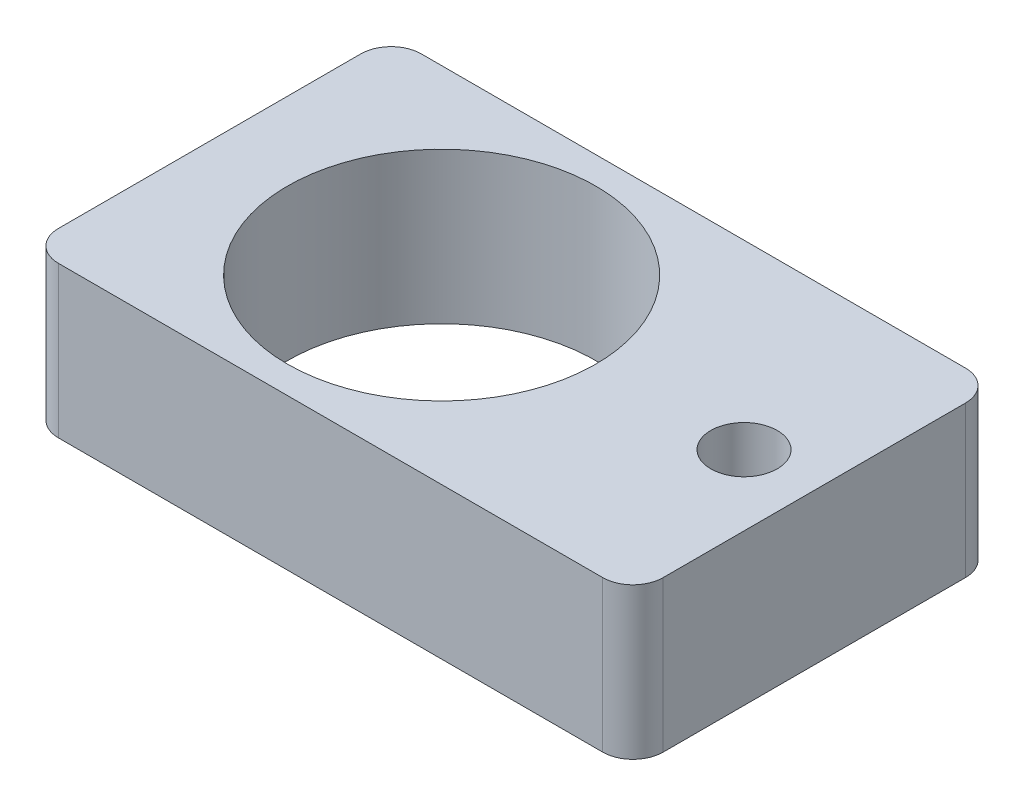
SolidWorks part; units mm, degrees
ref_plane "Front Plane" through (0, 0, 0) normal (0, 0, 1) x (1, 0, 0)
ref_plane "Top Plane" through (0, 0, 0) normal (0, 1, 0) x (1, 0, 0)
ref_plane "Right Plane" through (0, 0, 0) normal (1, 0, 0) x (0, 0, -1)
sketch "Sketch1" plane through (0, 0, 0) normal (0, 1, 0) x (1, 0, 0)
  line L0 (0, 7.4941) -> (0, -8.3492) construction
  line L1 (-12.7553, 0) -> (14.6081, 0) construction
  line L3 (-10, -6) -> (10, -6)
  line L4 (-10, -6) -> (-10, 6)
  line L5 (-10, 6) -> (10, 6)
  line L6 (10, -6) -> (10, 6)
  circle A0 centre (-2.327, 0) radius 5.1
  circle A1 centre (7.673, 0) radius 1.1
  point P9 (-10, 0)
  point P10 (0, 6)
  point P15 (7.5227, 0)
  point P16 (-2.327, 0)
  dimension "D3" = 2.2
  dimension "D4" = 10.2
  dimension "D1" = 12
  dimension "D2" = 20
  dimension "D5" = 10
extrude "Boss-Extrude1" add sketch "Sketch1" along normal blind 5
fillet "Fillet1" radius 1 4 edges at (10, 2.5, 6) (10, 2.5, -6) (-10, 2.5, -6) (-10, 2.5, 6)
